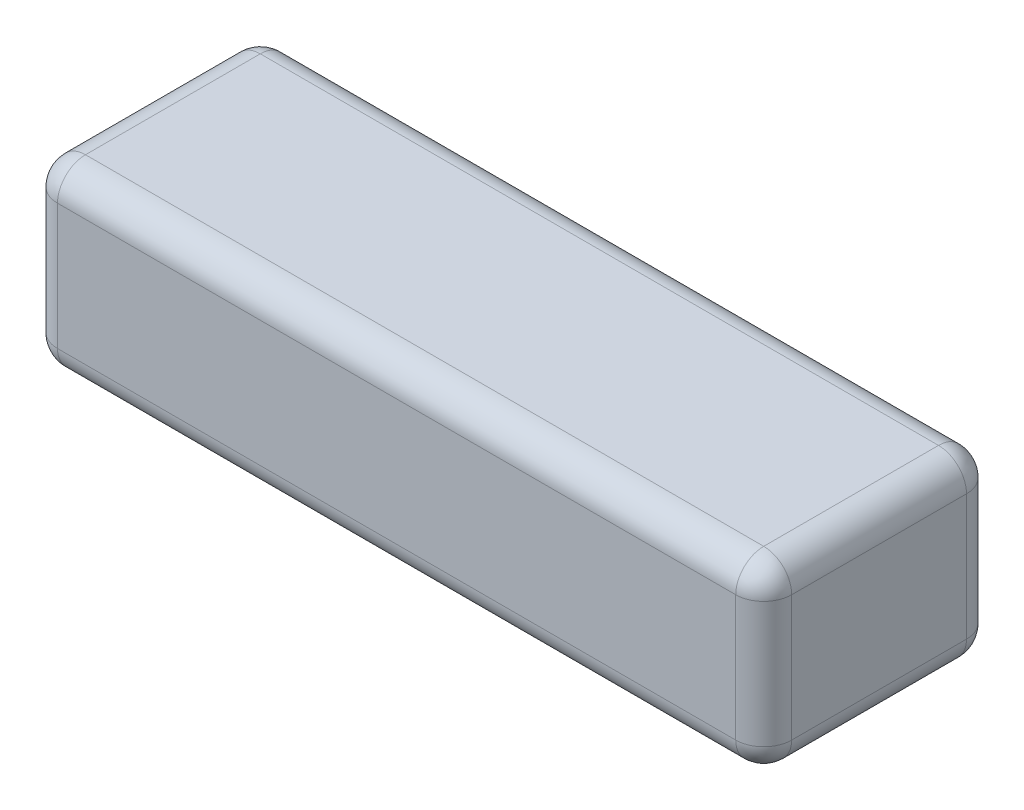
SolidWorks part; units mm, degrees
ref_plane "Front Plane" through (0, 0, 0) normal (0, 0, 1) x (1, 0, 0)
ref_plane "Top Plane" through (0, 0, 0) normal (0, 1, 0) x (1, 0, 0)
ref_plane "Right Plane" through (0, 0, 0) normal (1, 0, 0) x (0, 0, -1)
other "Center of Mass"
sketch "Sketch2" plane through (0, 0, 0) normal (0, 1, 0) x (1, 0, 0)
  line L1 (0, 0) -> (105, 0)
  line L2 (0, 0) -> (0, 33)
  line L3 (0, 33) -> (105, 33)
  line L4 (105, 0) -> (105, 33)
  dimension "D1" = 105
  dimension "D2" = 33
extrude "Boss-Extrude1" add sketch "Sketch2" along normal blind 26
fillet "Fillet1" radius 4 12 edges at (0, 13, 0) (0, 0, -16.5) (0, 26, -16.5) (0, 13, -33) (105, 13, -33) (105, 13, 0) (105, 0, -16.5) (105, 26, -16.5) (52.5, 0, -33) (52.5, 0, 0) (52.5, 26, -33) (52.5, 26, 0)
